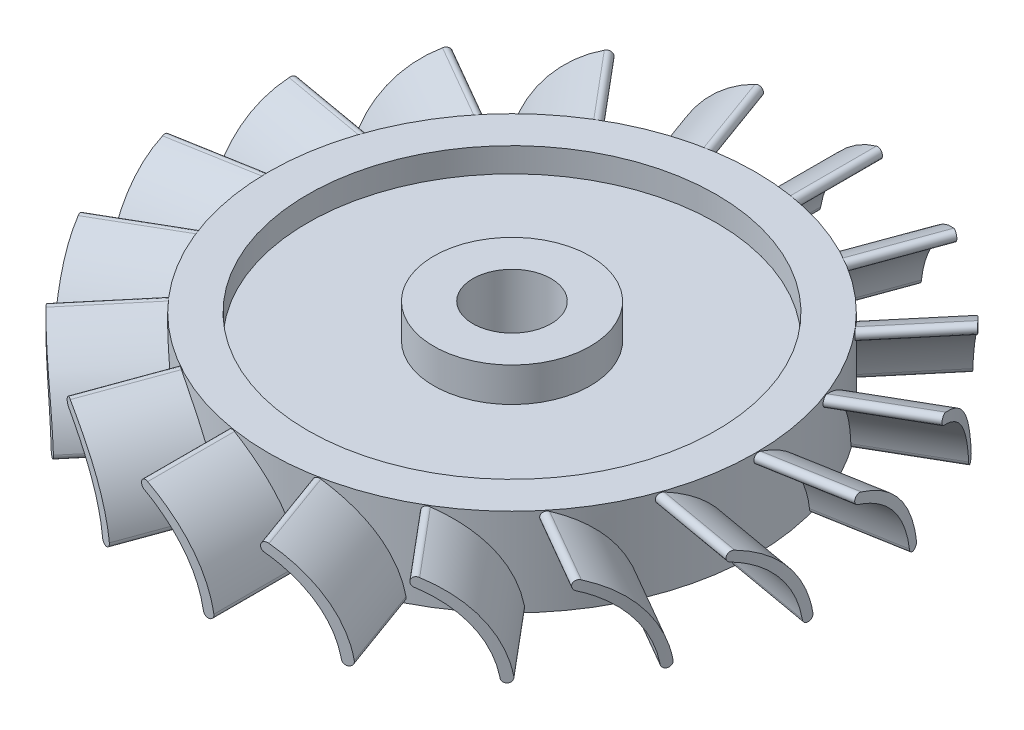
SolidWorks part; units mm, degrees
ref_plane "Ön Düzlem" through (0, 0, 0) normal (0, 0, 1) x (1, 0, 0)
ref_plane "Üst Düzlem" through (0, 0, 0) normal (0, 1, 0) x (1, 0, 0)
ref_plane "Sağ Düzlem" through (0, 0, 0) normal (1, 0, 0) x (0, 0, -1)
sketch "Çizim1" plane through (0, 0, 0) normal (0, 0, 1) x (1, 0, 0)
  line L0 (0, -2.2965) -> (0, 11.3295) construction
  line L1 (-20.9, -0.1095) -> (-24.9, -0.1095)
  line L2 (-20.9, -0.1095) -> (-20.9, -2.6095)
  line L3 (-20.9, -2.6095) -> (-8, -2.6095)
  line L4 (-8, -2.6095) -> (-8, 0.8905)
  line L5 (-8, 0.8905) -> (-4, 0.8905)
  line L6 (-4, 0.8905) -> (-4, -9.1095)
  line L7 (-4, -9.1095) -> (-8, -9.1095)
  line L8 (-8, -9.1095) -> (-8, -6.6095)
  line L9 (-8, -6.6095) -> (-20.9, -6.6095)
  line L10 (-20.9, -6.6095) -> (-20.9, -9.1095)
  line L11 (-20.9, -9.1095) -> (-24.9, -9.1095)
  line L12 (-24.9, -9.1095) -> (-24.9, -0.1095)
  dimension "D1" = 24.9
  dimension "D2" = 10
  dimension "D3" = 9
  dimension "D4" = 4
  dimension "D5" = 4
  dimension "D6" = 3.5
  dimension "D7" = 2.5
  dimension "D8" = 4
  dimension "D9" = 20.9
  dimension "D10" = 4
  dimension "D11" = 12.9
revolve "Döndür1" add sketch "Çizim1" angle 360 about L0
ref_plane "Düzlem1" through (0, 0, 24) normal (0, 0, 1) x (1, 0, 0)
sketch "Çizim2" plane through (0, 0, 24) normal (0, 0, 1) x (1, 0, 0)
  line L0 (0, -16.5366) -> (0, 12.1807) construction
  arc A1 (3.0682, -8.5217) -> (-3.7713, -0.2319) centre (-7.3098, -10.1177) ccw
  arc A2 (2.071, -8.6177) -> (-4.1083, -1.1734) centre (-7.3098, -10.1177) ccw
  arc A4 (2.071, -8.6177) -> (3.0682, -8.5217) centre (2.5723, -8.598) ccw
  arc A5 (-3.7713, -0.2319) -> (-4.1083, -1.1734) centre (-3.9881, -0.6853) ccw
extrude "Yükseklik-Ekstrüzyon5" add sketch "Çizim2" along normal blind 10.4
pattern_circular "Dairesel Kaplama2" count 18 over 360 about axis through (0, 0, 0) along (0, 1, 0) of "Yükseklik-Ekstrüzyon5"
sketch "Çizim3" plane through (0, 0, 0) normal (0, 0, 1) x (1, 0, 0)
  line L0 (0, -14.6419) -> (0, 10.9518) construction
  line L1 (33.7, -14.6419) -> (33.7, 15.6913)
  line L2 (35.7, -14.6419) -> (35.7, 15.6913)
  line L3 (33.7, 15.6913) -> (35.7, 15.6913)
  line L4 (35.7, -14.6419) -> (33.7, -14.6419)
  dimension "D1" = 33.7
  dimension "D2" = 2
revolve "Kes-Döndür1" cut sketch "Çizim3" angle 360 about L0
